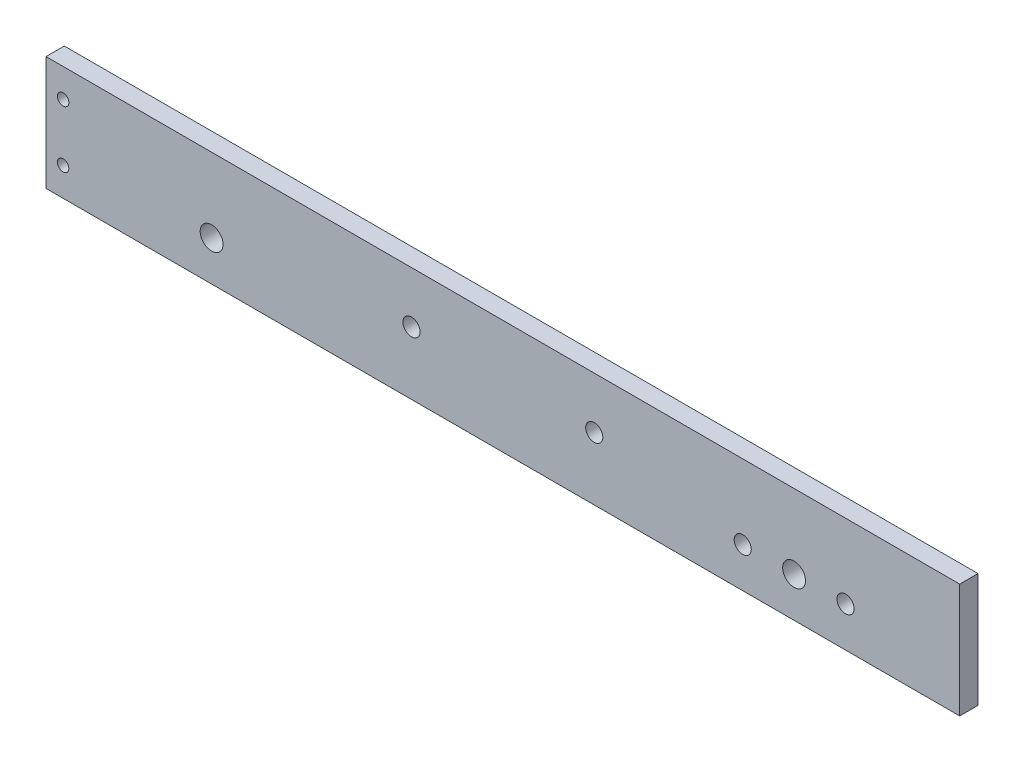
SolidWorks part; units mm, degrees
material "Balsa"
ref_plane "Front Plane" through (0, 0, 0) normal (0, 0, 1) x (1, 0, 0)
ref_plane "Top Plane" through (0, 0, 0) normal (0, 1, 0) x (1, 0, 0)
ref_plane "Right Plane" through (0, 0, 0) normal (1, 0, 0) x (0, 0, -1)
ref_plane "Plane1" through (0, 0, 10) normal (0, 0, 1) x (1, 0, 0)
sketch "Sketch2" plane through (0, -10, 10) normal (0, 0, -1) x (1, 0, 0)
  line L1 (0, -10) -> (160, -10)
  line L2 (0, -10) -> (0, 10)
  line L3 (0, 10) -> (160, 10)
  line L4 (160, -10) -> (160, 10)
  dimension "D1" = 20
  dimension "D2" = 160
extrude "Boss-Extrude1" add sketch "Sketch2" along normal blind 3.2
sketch "Sketch4" plane through (0, 0, 0) normal (0, 1, 0) x (1, 0, 0)
  line L0 (0, -10) -> (160, -10) construction
  line L1 (0, -6.8) -> (80, -6.8)
  line L2 (0, -6.8) -> (0, -10)
  line L3 (0, -10) -> (80, -10)
  line L4 (80, -6.8) -> (80, -10)
  line L5 (160, -6.8) -> (160, -10) construction
  dimension "D1" = 80
  dimension "D2" = 80
sketch "Sketch5" plane through (0, 0, 10) normal (0, 0, 1) x (1, 0, 0)
  line L0 (102, 2.15) -> (102, -20)
  line L1 (102, 0) -> (102, 4.3) construction
  line L2 (160, -20) -> (0, -20) construction
  line L3 (58, 2.15) -> (58, -20)
  line L4 (58, 0) -> (58, 4.3) construction
  line L7 (29, -13) -> (131, -13)
  line L9 (0, 0) -> (160, 0) construction
  circle A0 centre (131, -13) radius 2
  circle A1 centre (29, -13) radius 2
  dimension "D1" = 13
extrude "Cut-Extrude1" cut sketch "Sketch5" against normal through all both and the other way through all contours A0 | A1
sketch "Sketch6" plane through (0, 0, 10) normal (0, 0, 1) x (1, 0, 0)
  line L1 (0, 0) -> (80, 0) construction
  circle A2 centre (64, -9) radius 1.5
  circle A4 centre (96, -9) radius 1.5
  dimension "D1" = 32
  dimension "D3" = 3
  dimension "D4" = 9
extrude "Cut-Extrude2" cut sketch "Sketch6" against normal blind 10
sketch "Sketch7" plane through (0, 0, 10) normal (0, 0, 1) x (1, 0, 0)
  circle A0 centre (3, -15) radius 1
  circle A1 centre (3, -5) radius 1
  dimension "D1" = 2
extrude "Cut-Extrude3" cut sketch "Sketch7" against normal through all both and the other way through all
sketch "Sketch8" plane through (0, 0, 10) normal (0, 0, 1) x (1, 0, 0)
  circle A0 centre (140, -13) radius 1.5
  circle A1 centre (122, -13) radius 1.5
extrude "Cut-Extrude4" cut sketch "Sketch8" against normal blind 10
